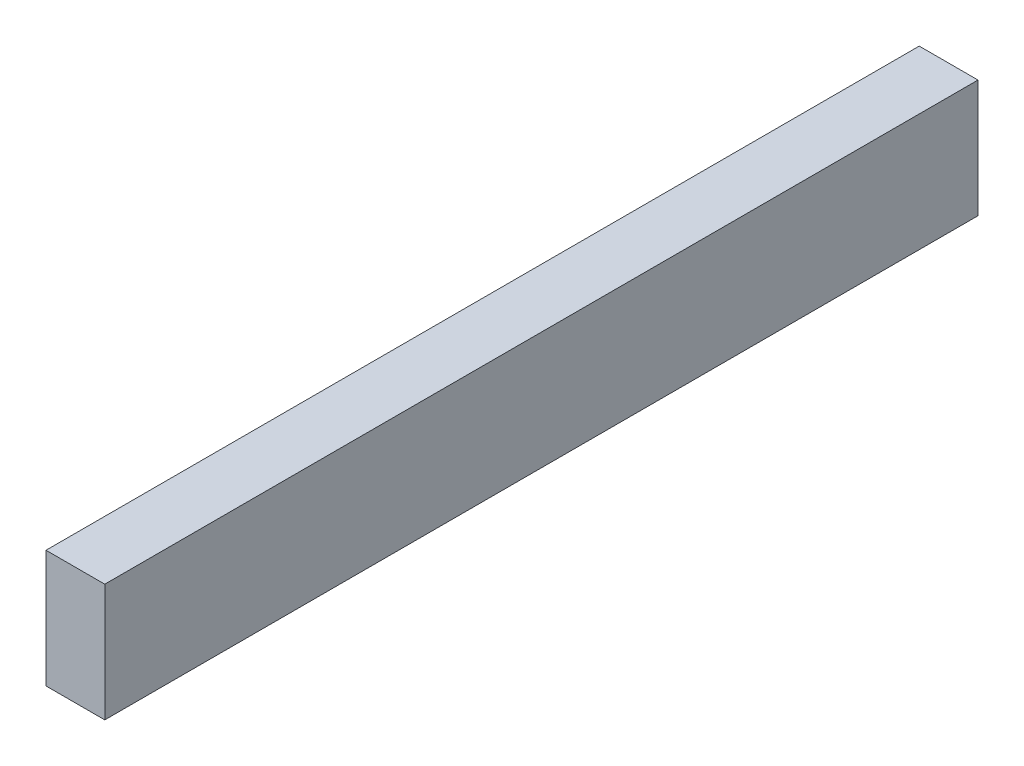
SolidWorks part; units mm, degrees
ref_plane "Front Plane" through (0, 0, 0) normal (0, 0, 1) x (1, 0, 0)
ref_plane "Top Plane" through (0, 0, 0) normal (0, 1, 0) x (1, 0, 0)
ref_plane "Right Plane" through (0, 0, 0) normal (1, 0, 0) x (0, 0, -1)
sketch "Sketch1" plane through (0, 0, 0) normal (0, 0, 1) x (1, 0, 0)
  line L1 (0, 0) -> (22.225, 0)
  line L2 (0, 0) -> (0, 44.45)
  line L3 (0, 44.45) -> (22.225, 44.45)
  line L4 (22.225, 0) -> (22.225, 44.45)
  dimension "D1" = 22.225
  dimension "D2" = 44.45
extrude "Boss-Extrude1" add sketch "Sketch1" along normal blind 330.2
